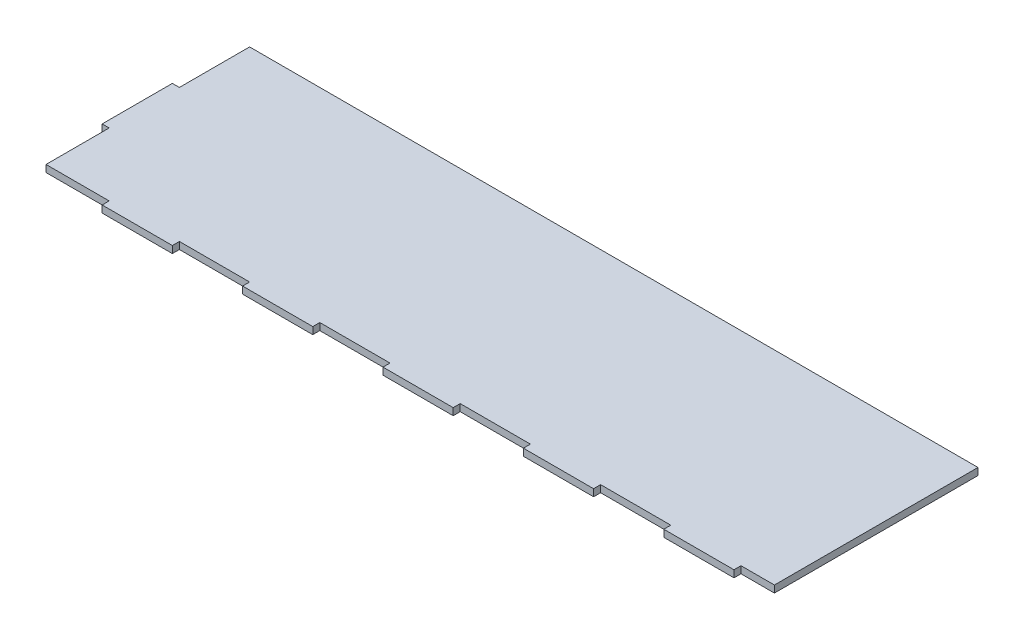
SolidWorks part; units mm, degrees
ref_plane "Front Plane" through (0, 0, 0) normal (0, 0, 1) x (1, 0, 0)
ref_plane "Top Plane" through (0, 0, 0) normal (0, 1, 0) x (1, 0, 0)
ref_plane "Right Plane" through (0, 0, 0) normal (1, 0, 0) x (0, 0, -1)
sketch "Sketch1" plane through (0, 0, 0) normal (0, 1, 0) x (1, 0, 0)
  line L1 (-315, -45) -> (315, -45)
  line L2 (-315, -45) -> (-315, 45)
  line L3 (-315, 45) -> (315, 45)
  line L4 (315, -45) -> (315, 45)
  line L5 (0, 45) -> (0, -45) construction
  line L6 (-315, 0) -> (315, 0) construction
  point P0 (0, 0)
  dimension "D1" = 630
  dimension "D2" = 90
extrude "Boss-Extrude1" add sketch "Sketch1" along normal blind 3
ref_plane "Plane1" through (-255, 0, 0) normal (-1, 0, 0) x (0, 0, 1)
sketch "Sketch3" plane through (0, 3, 0) normal (0, 1, 0) x (1, 0, 0)
  line L0 (-255, 1.65) -> (-255, -1.65) construction
  line L1 (-255, -45) -> (-225, -45)
  line L2 (-255, -45) -> (-255, -42)
  line L3 (-255, -42) -> (-225, -42)
  line L4 (-225, -45) -> (-225, -42)
  line L5 (-315, -45) -> (315, -45) construction
  dimension "D1" = 30
  dimension "D2" = 3
extrude "Cut-Extrude1" cut sketch "Sketch3" against normal blind 3
pattern_linear "LPattern1" count 10 spacing 60 along (1, 0, 0) count 2 spacing 60 along (-1, 0, 0) of "Cut-Extrude1"
ref_plane "Plane2" through (0, 0, -15) normal (0, 0, -1) x (-1, 0, 0)
sketch "Sketch7" plane through (0, 3, 0) normal (0, 1, 0) x (1, 0, 0)
  line L1 (-315, 45) -> (-312, 45)
  line L2 (-315, 45) -> (-315, 15)
  line L3 (-315, 15) -> (-312, 15)
  line L4 (-312, 45) -> (-312, 15)
  dimension "D1" = 30
  dimension "D2" = 3
extrude "Cut-Extrude3" cut sketch "Sketch7" against normal blind 3
ref_plane "Plane3" through (0, 0, 15) normal (0, 0, 1) x (1, 0, 0)
ref_plane "Plane4" through (-312, 3, -45) normal (0, 0, -1) x (-1, 0, 0)
sketch "Sketch13" plane through (0, 3, 0) normal (0, 1, 0) x (1, 0, 0)
  line L0 (-6.6903, -15) -> (6.6903, -15) construction
  line L1 (-315, -42) -> (-312, -42)
  line L2 (-315, -42) -> (-315, -15)
  line L3 (-315, -15) -> (-312, -15)
  line L4 (-312, -42) -> (-312, -15)
  dimension "D1" = 3
extrude "Cut-Extrude4" cut sketch "Sketch13" against normal blind 10
ref_plane "Plane5" through (-0.725, 0, 0) normal (1, 0, 0) x (0, 0, -1)
other "SurfaceCut1"
